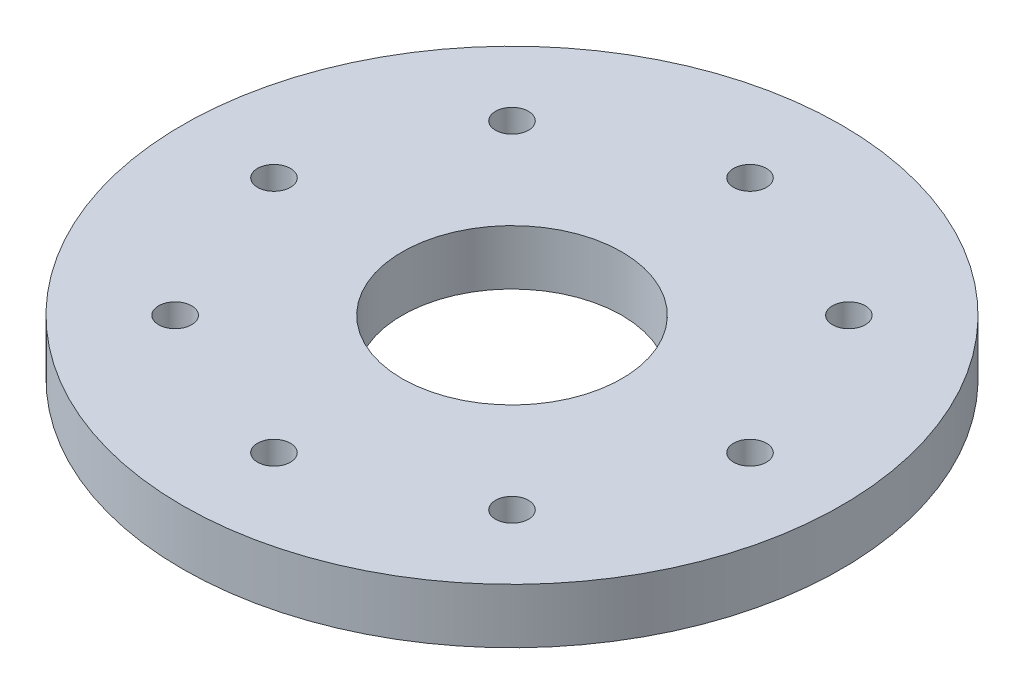
SolidWorks part; units mm, degrees
ref_plane "Front Plane" through (0, 0, 0) normal (0, 0, 1) x (1, 0, 0)
ref_plane "Top Plane" through (0, 0, 0) normal (0, 1, 0) x (1, 0, 0)
ref_plane "Right Plane" through (0, 0, 0) normal (1, 0, 0) x (0, 0, -1)
other "Configuration Table"
sketch "草图1" plane through (0, 0, 0) normal (0, 1, 0) x (1, 0, 0)
  circle A0 centre (0, 0) radius 180
  circle A1 centre (0, 0) radius 60
  circle A2 centre (130, 0) radius 9
  circle A3 centre (-130, 0) radius 9
  circle A4 centre (0, 130) radius 9
  circle A5 centre (0, -130) radius 9
  circle A6 centre (92, 92) radius 9
  circle A7 centre (-92, 92) radius 9
  circle A8 centre (92, -92) radius 9
  circle A9 centre (-92, -92) radius 9
extrude "凸台-拉伸1" add sketch "草图1" along normal blind 30
